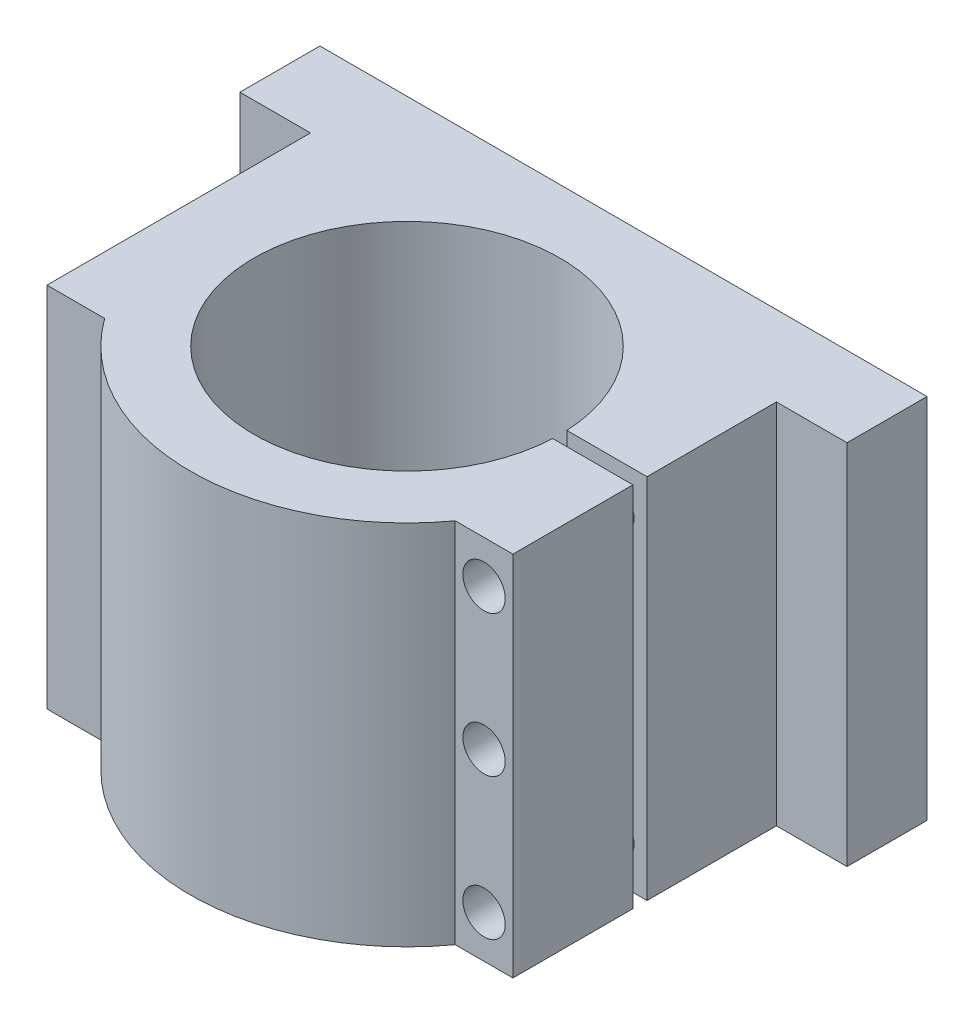
SolidWorks part; units mm, degrees
material "1060 Alloy"
ref_plane "Front" through (0, 0, 0) normal (0, 0, 1) x (1, 0, 0)
ref_plane "Top" through (0, 0, 0) normal (0, 1, 0) x (1, 0, 0)
ref_plane "Right" through (0, 0, 0) normal (1, 0, 0) x (0, 0, -1)
sketch "Sketch1" plane through (0, 0, 0) normal (0, 1, 0) x (1, 0, 0)
  line L0 (-64.5, 0) -> (-64.5, -17)
  line L1 (-64.5, -17) -> (-49.5, -17)
  line L2 (-49.5, -17) -> (-49.5, -73)
  line L3 (-49.5, -73) -> (-37.2424, -73)
  line L4 (-64.5, 0) -> (0, 0)
  line L5 (0, 0) -> (0, 58.8458) construction
  line L6 (49.5, -73) -> (49.5, -47.5)
  line L7 (49.5, -17) -> (64.5, -17)
  line L8 (64.5, -17) -> (64.5, 0)
  line L9 (64.5, 0) -> (0, 0)
  line L10 (37.2424, -73) -> (49.5, -73)
  line L11 (49.5, -44.5) -> (49.5, -17)
  line L12 (49.5, -44.5) -> (32.4654, -44.5)
  line L14 (49.5, -47.5) -> (32.4654, -47.5)
  arc A0 (32.4654, -44.5) -> (32.4654, -47.5) centre (0, -46) ccw
  arc A1 (-37.2424, -73) -> (37.2424, -73) centre (0, -46) ccw
  dimension "D4" = 65
  dimension "D5" = 92
  dimension "D1" = 129
  dimension "D2" = 17
  dimension "D3" = 99
  dimension "D6" = 73
  dimension "D7" = 3
  dimension "D8" = 1.5
extrude "Boss-Extrude1" add sketch "Sketch1" along normal blind 78
hole_wizard "Ø9.0 (9) Diameter Hole1" positions "Sketch2" profile "Sketch3" hole size "Ø9.0" standard "ISO"
sketch "Sketch2" plane through (0, 0, 73) normal (0, 0, 1) x (1, 0, 0)
  line L0 (43.3712, 78) -> (43.3712, 69) construction
  line L1 (37.2424, 78) -> (49.5, 78) construction
  point P0 (43.3712, 69)
  point P2 (43.3712, 39)
  point P4 (43.3712, 9)
  dimension "D1" = 60
  dimension "D2" = 30
  dimension "D3" = 39
sketch "Sketch3" plane through (43.3712, 69, 73) normal (1, 0, 0) x (0, -1, 0)
  line L0 (0, 0) -> (0, 25.5)
  line L1 (0, 25.5) -> (4.5, 25.5)
  line L2 (4.5, 25.5) -> (4.5, 0)
  line L5 (4.5, 0) -> (0, 0)
  line L11 (0, -6.35) -> (0, 107.95) construction
  dimension "Thru Hole Dia." = 9
  dimension "Thru Hole Depth" = 25.5
hole_wizard "M8 Tapped Hole1" positions "Sketch4" profile "Sketch6" tap size "M8" standard "ISO"
sketch "Sketch4" plane through (0, 0, 44.5) normal (0, 0, 1) x (1, 0, 0)
  point P0 (43.3712, 69)
  point P3 (43.3712, 9)
sketch "Sketch6" plane through (43.3712, 69, 44.5) normal (1, 0, 0) x (0, -1, 0)
  line L0 (0, 0) -> (0, 21.7929)
  line L1 (0, 21.7929) -> (3.4, 19.75)
  line L2 (3.4, 19.75) -> (3.4, 0)
  line L5 (3.4, 0) -> (0, 0)
  line L10 (0, 21.7929) -> (-3.4, 19.75) construction
  line L11 (0, -6.35) -> (0, 107.95) construction
  dimension "Tap Drill Dia." = 6.8
  dimension "Tap Drill Depth" = 19.75
  dimension "Drill Angle" = 118
cosmetic thread "Hole Thread1" parameters "D1"=16, "D2"=8
cosmetic thread "Hole Thread2" parameters "D1"=16, "D2"=8
